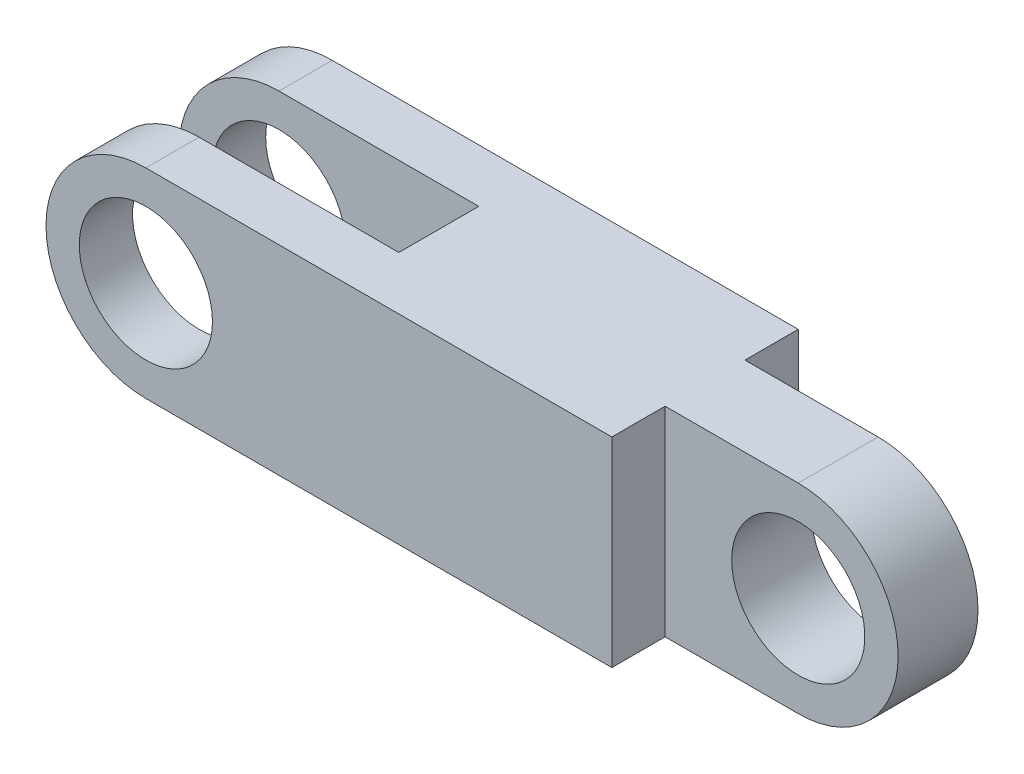
SolidWorks part; units mm, degrees
ref_plane "Plan de face" through (0, 0, 0) normal (0, 0, 1) x (1, 0, 0)
ref_plane "Plan de dessus" through (0, 0, 0) normal (0, 1, 0) x (1, 0, 0)
ref_plane "Plan de droite" through (0, 0, 0) normal (1, 0, 0) x (0, 0, -1)
sketch "Esquisse1" plane through (0, 0, 0) normal (0, 0, 1) x (1, 0, 0)
  line L1 (0, 0) -> (45, 0)
  line L2 (0, 0) -> (0, 15)
  line L3 (0, 15) -> (45, 15)
  line L4 (45, 0) -> (45, 15)
  circle A0 centre (0, 7.5) radius 5
  circle A1 centre (0, 7.5) radius 7.5
  circle A2 centre (45, 7.5) radius 7.5
  circle A3 centre (45, 7.5) radius 5
  dimension "D3" = 10
  dimension "D4" = 10
  dimension "D1" = 45
  dimension "D2" = 15
extrude "Boss.-Extru.1" add sketch "Esquisse1" along normal blind 14 contours A2 L3 A1 L1 | A3 L4 A2 | A3 L4 A2 | L2 A1 A0 | L2 A1 A0
sketch "Esquisse2" plane through (0, 15, 0) normal (0, 1, 0) x (1, 0, 0)
  line L0 (-7.5, 0) -> (-7.5, -14) construction
  line L9 (0, 0) -> (-7.5, 0)
  line L10 (0, 0) -> (0, -4)
  line L11 (0, -4) -> (-7.5, -4)
  line L12 (-7.5, 0) -> (-7.5, -4)
  line L14 (-7.5, -4) -> (15, -4)
  line L15 (-7.5, -4) -> (-7.5, -10)
  line L16 (-7.5, -10) -> (15, -10)
  line L17 (15, -4) -> (15, -10)
  line L18 (52.5, 0) -> (35, 0)
  line L19 (52.5, 0) -> (52.5, -4)
  line L20 (52.5, -4) -> (35, -4)
  line L21 (35, 0) -> (35, -4)
  line L22 (52.5, -14) -> (35, -14)
  line L23 (52.5, -14) -> (52.5, -10)
  line L24 (52.5, -10) -> (35, -10)
  line L25 (35, -14) -> (35, -10)
  line M14 (45, 0) -> (0, 0)
  line M15 (0, 0) -> (0, -14)
  line M16 (0, -14) -> (45, -14)
  line M17 (45, -14) -> (45, 0)
  dimension "D1" = 4
  dimension "D2" = 22.5
  dimension "D3" = 6
  dimension "D4" = 17.5
extrude "Enlèv. mat.-Extru.1" cut sketch "Esquisse2" against normal blind 15 contours L15 L16 L11 M15 | L17 L14 L16 M15 | L21 L20 M14 M17 | L20 L19 L18 M17 | L23 L24 L22 M17 | L25 L24 M16 M17
equation "\"diamètre\"=10"
equation "\"D3@Esquisse1\"=\"diamètre\""
equation "\"D4@Esquisse1\"=\"diamètre\""
